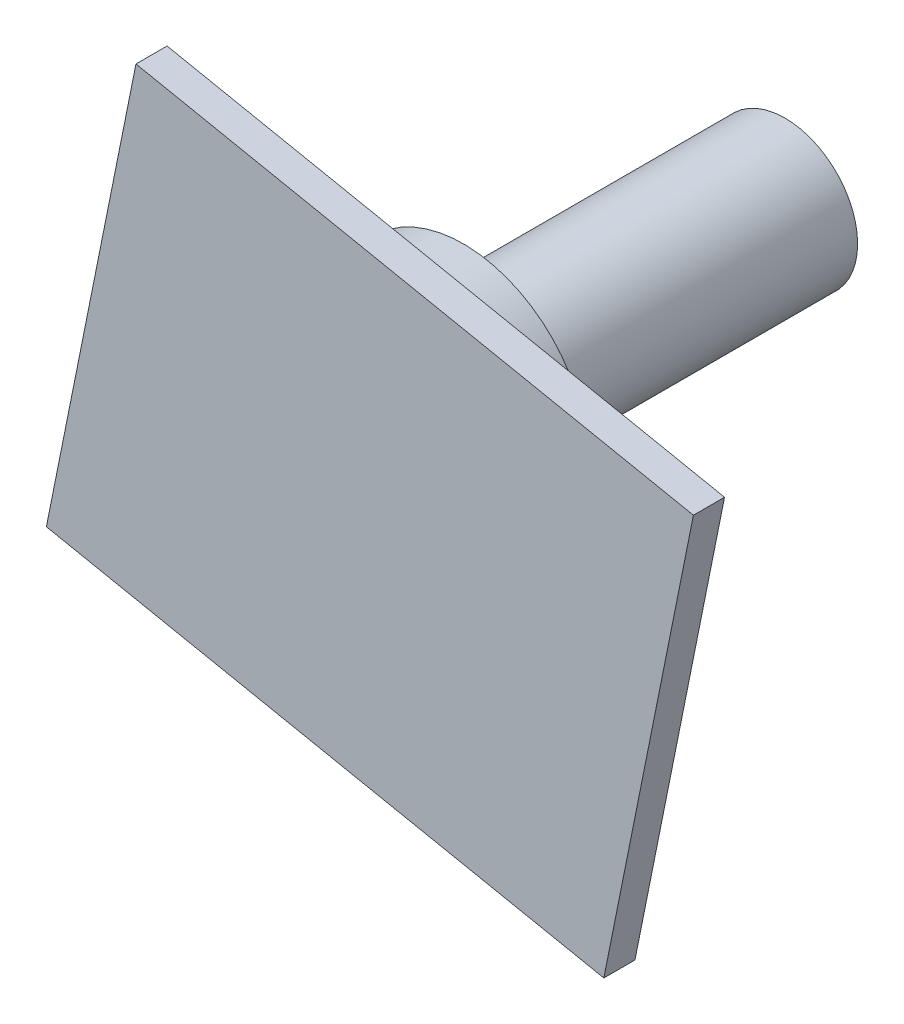
SolidWorks part; units mm, degrees
ref_plane "前视基准面" through (0, 0, 0) normal (0, 0, 1) x (1, 0, 0)
ref_plane "上视基准面" through (0, 0, 0) normal (0, 1, 0) x (1, 0, 0)
ref_plane "右视基准面" through (0, 0, 0) normal (1, 0, 0) x (0, 0, -1)
other "Configuration Table"
sketch "草图1" plane through (0, 0, 0) normal (0, 0, 1) x (1, 0, 0)
  circle A0 centre (-86.6066, -63.7835) radius 7
extrude "凸台-拉伸1" add sketch "草图1" along normal blind 34
sketch "草图2" plane through (0, 0, 34) normal (0, 0, 1) x (1, 0, 0)
  circle A0 centre (-86.6066, -63.7835) radius 12
extrude "凸台-拉伸2" add sketch "草图2" against normal blind 3 and the other way blind 2
sketch "草图3" plane through (0, 0, 36) normal (0, 0, 1) x (1, 0, 0)
  line L0 (-110.1056, -28.4593) -> (-40.7849, -42.3949) construction
  line L3 (-110.1765, -44.5529) -> (-56.4369, -55.3563)
  line L4 (-110.1765, -44.5529) -> (-118.8118, -87.5076)
  line L5 (-56.4369, -55.3563) -> (-65.0721, -98.3109)
  line L6 (-118.8118, -87.5076) -> (-65.0721, -98.3109)
  arc A0 (-125.6196, -54.9524) -> (-91.6831, -24.107) centre (-86.6066, -63.7835) ccw construction
  point P2 (-118.8118, -87.5076)
extrude "凸台-拉伸4" add sketch "草图3" along normal blind 3
